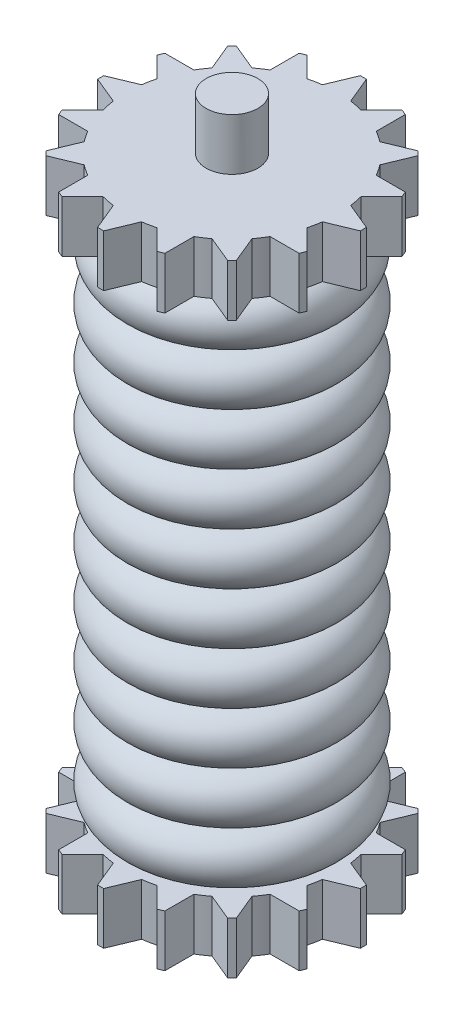
SolidWorks part; units mm, degrees
ref_plane "Front Plane" through (0, 0, 0) normal (1, 0, 0) x (0, 1, 0)
ref_plane "Top Plane" through (0, 0, 0) normal (0, 0, 1) x (0, 1, 0)
ref_plane "Right Plane" through (0, 0, 0) normal (0, 1, 0) x (-1, 0, 0)
sketch "Sketch6" plane through (0, 0, 0) normal (0, 0, 1) x (0, 1, 0)
  line L1 (0, 0) -> (100, 0)
  line L2 (0, 0) -> (0, -16.625)
  line L3 (0, -16.625) -> (100, -16.625)
  line L4 (100, 0) -> (100, -16.625)
  arc A0 (0, -16.625) -> (10, -16.625) centre (5, -16.625) ccw
  arc A1 (10, -16.625) -> (20, -16.625) centre (15, -16.625) ccw
  arc A2 (20, -16.625) -> (30, -16.625) centre (25, -16.625) ccw
  arc A3 (30, -16.625) -> (40, -16.625) centre (35, -16.625) ccw
  arc A4 (40, -16.625) -> (50, -16.625) centre (45, -16.625) ccw
  arc A5 (50, -16.625) -> (60, -16.625) centre (55, -16.625) ccw
  arc A6 (60, -16.625) -> (70, -16.625) centre (65, -16.625) ccw
  arc A7 (70, -16.625) -> (80, -16.625) centre (75, -16.625) ccw
  arc A8 (80, -16.625) -> (90, -16.625) centre (85, -16.625) ccw
  arc A9 (90, -16.625) -> (100, -16.625) centre (95, -16.625) ccw
  dimension "D3" = 5
  dimension "D1" = 16.625
  dimension "D2" = 10
  dimension "D4" = 100
revolve "Revolve1" add sketch "Sketch6" angle 360 about L1
sketch "Sketch3" plane through (0, 0, 0) normal (0, -1, 0) x (1, 0, 0)
  line L0 (0, -57.0817) -> (0, 57.0817) construction
  line L1 (0, 25.375) -> (2.1167, 20.2647) construction
  line L2 (0, 25.375) -> (-2.1167, 20.2647) construction
  line L5 (-2.733, 20.1909) -> (2.733, 20.1909) construction
  line L32 (-2.733, 20.1909) -> (-0.5885, 25.3682)
  line L33 (2.733, 20.1909) -> (0.5885, 25.3682)
  line L34 (5.2017, 19.6998) -> (9.1643, 23.6623)
  line L35 (10.2517, 17.6081) -> (10.2517, 23.2119)
  line L36 (12.3446, 16.2096) -> (17.5219, 18.3541)
  line L37 (16.2096, 12.3446) -> (18.3541, 17.5219)
  line L38 (17.6081, 10.2517) -> (23.2119, 10.2517)
  line L39 (19.6998, 5.2017) -> (23.6623, 9.1643)
  line L40 (20.1909, 2.733) -> (25.3682, 0.5885)
  line L41 (20.1909, -2.733) -> (25.3682, -0.5885)
  line L42 (19.6998, -5.2017) -> (23.6623, -9.1643)
  line L43 (17.6081, -10.2517) -> (23.2119, -10.2517)
  line L44 (16.2096, -12.3446) -> (18.3541, -17.5219)
  line L45 (12.3446, -16.2096) -> (17.5219, -18.3541)
  line L46 (10.2517, -17.6081) -> (10.2517, -23.2119)
  line L47 (5.2017, -19.6998) -> (9.1643, -23.6623)
  line L48 (2.733, -20.1909) -> (0.5885, -25.3682)
  line L49 (-2.733, -20.1909) -> (-0.5885, -25.3682)
  line L50 (-5.2017, -19.6998) -> (-9.1643, -23.6623)
  line L51 (-10.2517, -17.6081) -> (-10.2517, -23.2119)
  line L52 (-12.3446, -16.2096) -> (-17.5219, -18.3541)
  line L53 (-16.2096, -12.3446) -> (-18.3541, -17.5219)
  line L54 (-17.6081, -10.2517) -> (-23.2119, -10.2517)
  line L55 (-19.6998, -5.2017) -> (-23.6623, -9.1643)
  line L56 (-20.1909, -2.733) -> (-25.3682, -0.5885)
  line L57 (-20.1909, 2.733) -> (-25.3682, 0.5885)
  line L58 (-19.6998, 5.2017) -> (-23.6623, 9.1643)
  line L59 (-17.6081, 10.2517) -> (-23.2119, 10.2517)
  line L60 (-16.2096, 12.3446) -> (-18.3541, 17.5219)
  line L61 (-12.3446, 16.2096) -> (-17.5219, 18.3541)
  line L62 (-10.2517, 17.6081) -> (-10.2517, 23.2119)
  line L63 (-5.2017, 19.6998) -> (-9.1643, 23.6623)
  arc A28 (-16.2096, 12.3446) -> (-17.6081, 10.2517) centre (0, 0) ccw
  arc A29 (-23.2119, 10.2517) -> (-23.6623, 9.1643) centre (0, 0) ccw
  arc A30 (-17.5219, 18.3541) -> (-18.3541, 17.5219) centre (0, 0) ccw
  arc A31 (-10.2517, 17.6081) -> (-12.3446, 16.2096) centre (0, 0) ccw
  arc A32 (-9.1643, 23.6623) -> (-10.2517, 23.2119) centre (0, 0) ccw
  arc A33 (0.5885, 25.3682) -> (-0.5885, 25.3682) centre (0, 0) ccw
  arc A34 (10.2517, 23.2119) -> (9.1643, 23.6623) centre (0, 0) ccw
  arc A35 (-2.733, 20.1909) -> (-5.2017, 19.6998) centre (0, 0) ccw
  arc A36 (5.2017, 19.6998) -> (2.733, 20.1909) centre (0, 0) ccw
  arc A37 (18.3541, 17.5219) -> (17.5219, 18.3541) centre (0, 0) ccw
  arc A38 (12.3446, 16.2096) -> (10.2517, 17.6081) centre (0, 0) ccw
  arc A39 (17.6081, 10.2517) -> (16.2096, 12.3446) centre (0, 0) ccw
  arc A40 (23.6623, 9.1643) -> (23.2119, 10.2517) centre (0, 0) ccw
  arc A41 (25.3682, -0.5885) -> (25.3682, 0.5885) centre (0, 0) ccw
  arc A42 (23.2119, -10.2517) -> (23.6623, -9.1643) centre (0, 0) ccw
  arc A43 (20.1909, 2.733) -> (19.6998, 5.2017) centre (0, 0) ccw
  arc A44 (19.6998, -5.2017) -> (20.1909, -2.733) centre (0, 0) ccw
  arc A45 (17.5219, -18.3541) -> (18.3541, -17.5219) centre (0, 0) ccw
  arc A46 (9.1643, -23.6623) -> (10.2517, -23.2119) centre (0, 0) ccw
  arc A47 (10.2517, -17.6081) -> (12.3446, -16.2096) centre (0, 0) ccw
  arc A48 (16.2096, -12.3446) -> (17.6081, -10.2517) centre (0, 0) ccw
  arc A49 (-0.5885, -25.3682) -> (0.5885, -25.3682) centre (0, 0) ccw
  arc A50 (-10.2517, -23.2119) -> (-9.1643, -23.6623) centre (0, 0) ccw
  arc A51 (-5.2017, -19.6998) -> (-2.733, -20.1909) centre (0, 0) ccw
  arc A52 (2.733, -20.1909) -> (5.2017, -19.6998) centre (0, 0) ccw
  arc A53 (-18.3541, -17.5219) -> (-17.5219, -18.3541) centre (0, 0) ccw
  arc A54 (-23.6623, -9.1643) -> (-23.2119, -10.2517) centre (0, 0) ccw
  arc A55 (-12.3446, -16.2096) -> (-10.2517, -17.6081) centre (0, 0) ccw
  arc A56 (-17.6081, -10.2517) -> (-16.2096, -12.3446) centre (0, 0) ccw
  arc A57 (-20.1909, -2.733) -> (-19.6998, -5.2017) centre (0, 0) ccw
  arc A58 (-25.3682, 0.5885) -> (-25.3682, -0.5885) centre (0, 0) ccw
  arc A59 (-19.6998, 5.2017) -> (-20.1909, 2.733) centre (0, 0) ccw
  point P13 (0, 57.0817)
  point P17 (0, 47.4976)
  point P78 (0, 0)
  dimension "D2" = 50.75
  dimension "D1" = 40.75
  dimension "D3" = 22.5
  dimension "D4" = 22.5
  dimension "D5" = 5.466
  dimension "D6" = 16
extrude "Boss-Extrude3" add sketch "Sketch3" along normal blind 10
ref_plane "Plane1" through (0, 50, 0) normal (0, 1, 0) x (1, 0, 0)
mirror "Mirror1" about plane through (0, 50, 0) normal (0, 1, 0) of "Boss-Extrude3"
sketch "Sketch4" plane through (0, -10, 0) normal (0, -1, 0) x (1, 0, 0)
  circle A0 centre (0, 0) radius 5
  dimension "D1" = 10
extrude "Boss-Extrude4" add sketch "Sketch4" along normal blind 10
mirror "Mirror2" about plane through (0, 50, 0) normal (0, 1, 0) of "Boss-Extrude4"
